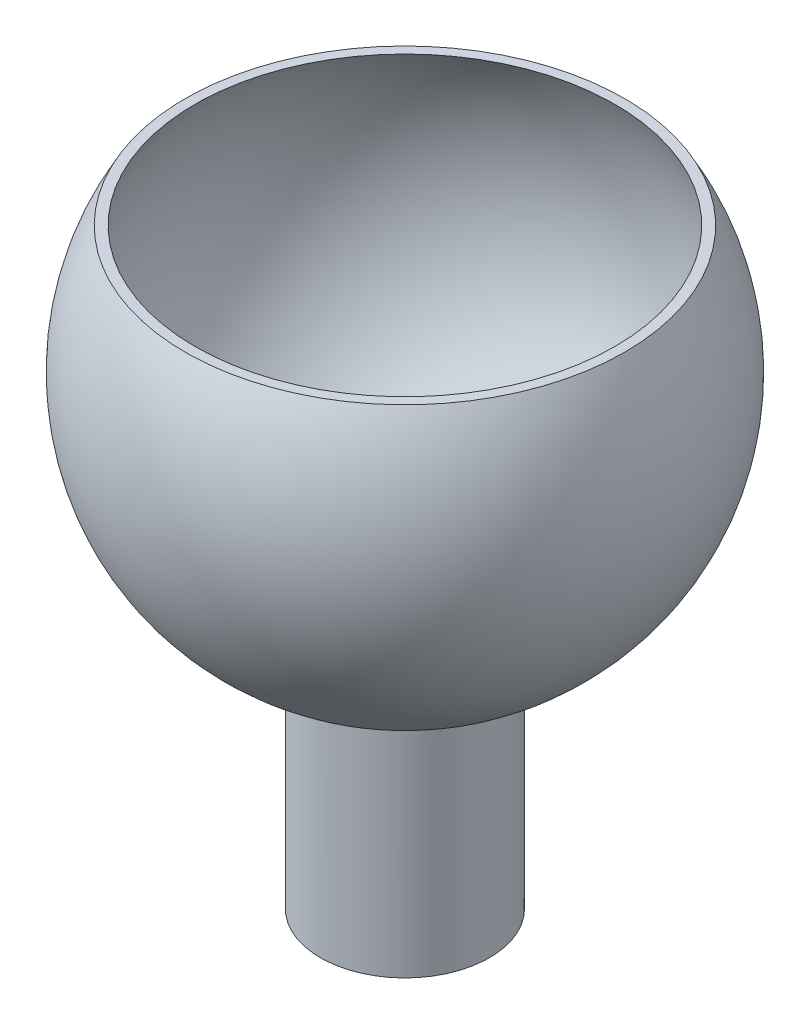
SolidWorks part; units mm, degrees
material "Cast Alloy Steel"
ref_plane "Front Plane" through (0, 0, 0) normal (0, 0, 1) x (1, 0, 0)
ref_plane "Top Plane" through (0, 0, 0) normal (0, 1, 0) x (1, 0, 0)
ref_plane "Right Plane" through (0, 0, 0) normal (1, 0, 0) x (0, 0, -1)
sketch "Sketch1" plane through (0, 0, 0) normal (0, 0, 1) x (1, 0, 0)
  line L0 (0, 30) -> (0, -30)
  arc A0 (0, -30) -> (0, 30) centre (0, 0) ccw
  point P4 (0, 0)
  dimension "D1" = 60
revolve "Revolve1" add sketch "Sketch1" angle 360 about L0
sketch "Sketch2" plane through (0, 0, 0) normal (0, 0, 1) x (1, 0, 0)
  line L0 (-39.0414, 15) -> (42.5826, 15)
  dimension "D1" = 15
extrude "Cut-Extrude1" cut sketch "Sketch2" against normal through all both and the other way through all
shell "Shell1" thickness 1
sketch "Sketch3" plane through (0, 0, 0) normal (0, 0, 1) x (1, 0, 0)
  line L0 (0, -30) -> (0, -55)
  line L1 (0, -55) -> (10, -55)
  line L2 (10, -55) -> (10, -28.2843)
  arc A0 (-25.9808, 15) -> (25.9808, 15) centre (0, 0) ccw construction
  arc A1 (0, -30) -> (10, -28.2843) centre (0, 0) ccw
  dimension "D1" = 30
  dimension "D2" = 25
  dimension "D3" = 10
revolve "Revolve2" add sketch "Sketch3" angle 360 about L0
